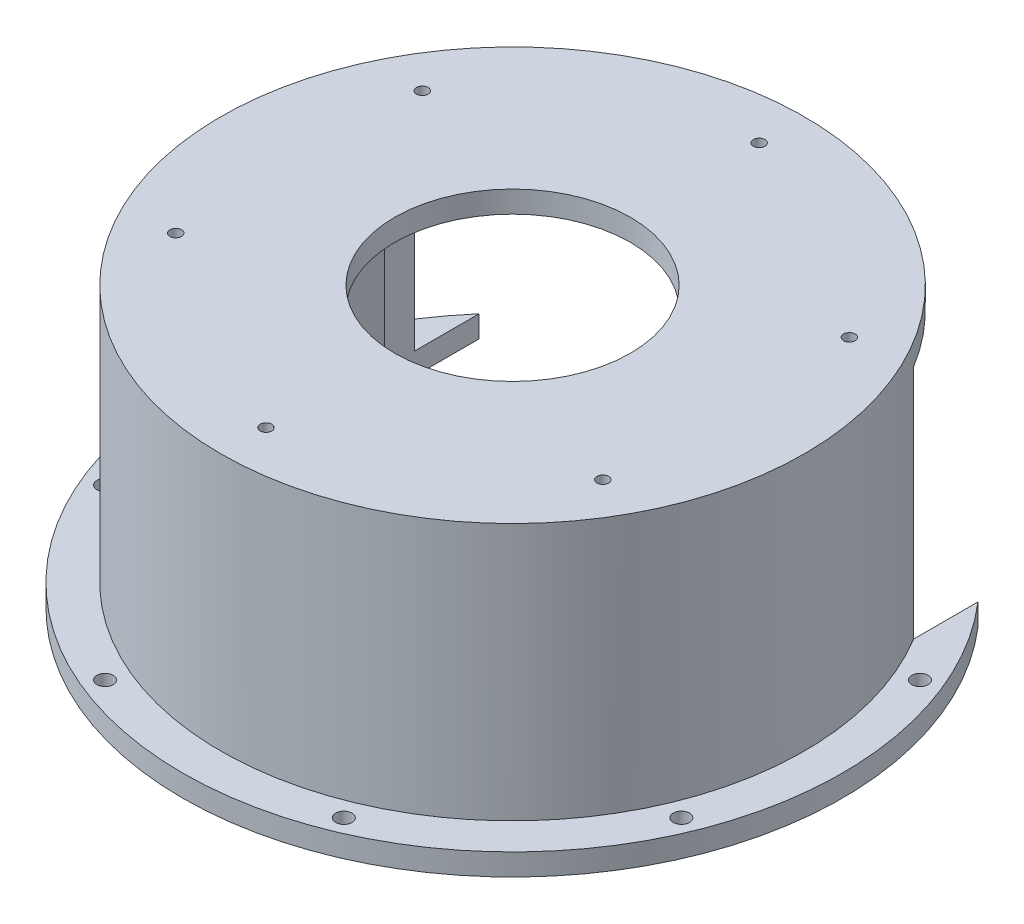
SolidWorks part; units mm, degrees
material "6061-T6 (SS)"
ref_plane "Front Plane" through (0, 0, 0) normal (0, 0, 1) x (1, 0, 0)
ref_plane "Top Plane" through (0, 0, 0) normal (0, 1, 0) x (1, 0, 0)
ref_plane "Right Plane" through (0, 0, 0) normal (1, 0, 0) x (0, 0, -1)
sketch "Sketch1" plane through (0, 0, 0) normal (0, 1, 0) x (1, 0, 0)
  circle A0 centre (0, 0) radius 144.4625
  dimension "D1" = 288.925
extrude "Boss-Extrude1" add sketch "Sketch1" along normal blind 9.525
sketch "Sketch2" plane through (0, 9.525, 0) normal (0, 1, 0) x (1, 0, 0)
  line L0 (0, 0) -> (-52.2459, 126.1327) construction
  line L2 (0, -5.2388) -> (0, 5.2388) construction
  circle A0 centre (0, 0) radius 136.525
  point P3 (-52.2459, 126.1327)
  point P4 (52.2459, 126.1327)
  point P5 (126.1327, 52.2459)
  point P8 (126.1327, -52.2459)
  point P9 (52.2459, -126.1327)
  point P10 (-52.2459, -126.1327)
  point P11 (-126.1327, -52.2459)
  point P12 (-126.1327, 52.2459)
  point P22 (0, 136.525)
  dimension "D1" = 273.05
  dimension "D3" = 22.5
  dimension "D4" = 22.5
  dimension "D2" = 8
hole_wizard "1/4 Clearance Hole1" positions "Sketch2" profile "Sketch3" hole size "1/4" standard "ANSI Inch" end condition up to next
sketch "Sketch3" plane through (0, 9.525, -136.525) normal (1, 0, 0) x (0, 0, 1)
  line L0 (0, 0) -> (0, 9.525)
  line L1 (0, 9.525) -> (3.5712, 9.525)
  line L2 (3.5712, 9.525) -> (3.5712, 0)
  line L5 (3.5712, 0) -> (0, 0)
  line L11 (0, -6.35) -> (0, 107.95) construction
  dimension "Thru Hole Dia." = 7.1425
  dimension "Thru Hole Depth" = 9.525
sketch "Sketch4" plane through (0, 9.525, 0) normal (0, 1, 0) x (1, 0, 0)
  circle A0 centre (0, 0) radius 127.7937
  circle A1 centre (0, 0) radius 121.4438
  dimension "D1" = 255.5875
  dimension "D2" = 242.8875
extrude "Boss-Extrude2" add sketch "Sketch4" along normal blind 112.7125
sketch "Sketch5" plane through (0, 122.2375, 0) normal (0, 1, 0) x (1, 0, 0)
  circle A0 centre (0, 0) radius 121.4438 construction
  circle A1 centre (0, 0) radius 127.7937
  circle A2 centre (0, 0) radius 127.7937
  circle A3 centre (0, 0) radius 121.4438
  dimension "D1" = 0
extrude "Boss-Extrude3" add sketch "Sketch5" against normal blind 9.525 contours A3
sketch "Sketch6" plane through (0, 0, 0) normal (0, -1, 0) x (1, 0, 0)
  circle A0 centre (0, 0) radius 121.4438
  dimension "D1" = 242.8875
extrude "Cut-Extrude1" cut sketch "Sketch6" against normal up to next
sketch "Sketch7" plane through (0, 122.2375, 0) normal (0, 1, 0) x (1, 0, 0)
  circle A0 centre (0, 0) radius 51.5938
  dimension "D1" = 103.1875
extrude "Cut-Extrude2" cut sketch "Sketch7" against normal up to next
sketch "Sketch10" plane through (0, 0, 0) normal (0, 1, 0) x (1, 0, 0)
  line L0 (-109.22, 53.0997) -> (109.22, 53.0997)
  line L1 (-109.22, 53.0997) -> (-109.22, 144.4625)
  line L2 (109.22, 53.0997) -> (109.22, 144.4625)
  line L3 (-109.22, 144.4625) -> (109.22, 144.4625)
  circle A0 centre (0, 0) radius 121.4438 construction
  circle A1 centre (0, 0) radius 144.4625 construction
  point P6 (0, 144.4625)
  dimension "D1" = 218.44
extrude "Cut-Extrude3" cut sketch "Sketch10" along normal up to surface (112.7125 mm away) contours L1 L3 L2 L0 up to face at (0, 112.7125, 51.5938)
sketch "Sketch11" plane through (0, 122.2375, 0) normal (0, 1, 0) x (1, 0, 0)
  circle A0 centre (0, 0) radius 107.95
  point P3 (0, -107.95)
  point P4 (-93.4874, -53.975)
  point P7 (-93.4874, 53.975)
  point P8 (0, 107.95)
  point P9 (93.4874, 53.975)
  point P10 (93.4874, -53.975)
  dimension "D1" = 215.9
  dimension "D2" = 6
hole_wizard "Tap Drill for 1/4-20 Tap1" positions "Sketch11" profile "Sketch12" hole size "1/4-20" standard "ANSI Inch" end condition up to next
sketch "Sketch12" plane through (93.4874, 122.2375, 53.975) normal (1, 0, 0) x (0, 0, 1)
  line L0 (0, 0) -> (0, 9.525)
  line L1 (0, 9.525) -> (2.5527, 9.525)
  line L2 (2.5527, 9.525) -> (2.5527, 0)
  line L5 (2.5527, 0) -> (0, 0)
  line L11 (0, -6.35) -> (0, 107.95) construction
  dimension "Thru Hole Dia." = 5.1054
  dimension "Thru Hole Depth" = 9.525
